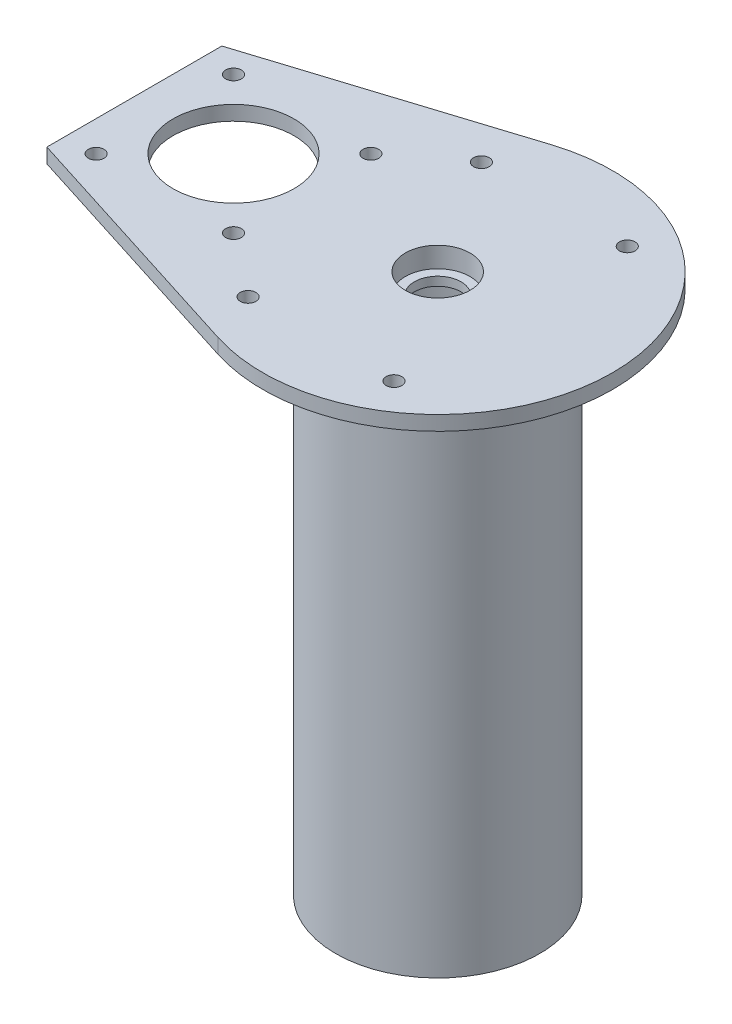
SolidWorks part; units mm, degrees
ref_plane "Front Plane" through (0, 0, 0) normal (0, 0, 1) x (1, 0, 0)
ref_plane "Top Plane" through (0, 0, 0) normal (0, 1, 0) x (1, 0, 0)
ref_plane "Right Plane" through (0, 0, 0) normal (1, 0, 0) x (0, 0, -1)
sketch "Sketch2" plane through (0, 0, 0) normal (0, 1, 0) x (1, 0, 0)
  line L0 (-104, -30) -> (-18.1154, -57.1999)
  line L2 (-104, -30) -> (-104, 30)
  line L5 (-93.55, 23.55) -> (-93.55, -23.55) construction
  line L6 (-93.55, -23.55) -> (-46.45, -23.55) construction
  line L7 (-104, 30) -> (-18.1154, 57.1999)
  line L8 (-46.45, -23.55) -> (-46.45, 23.55) construction
  line L9 (-46.45, 23.55) -> (-93.55, 23.55) construction
  arc A0 (-18.1154, -57.1999) -> (-18.1154, 57.1999) centre (0, 0) ccw
  circle A1 centre (-93.55, 23.55) radius 2.685
  circle A2 centre (-46.45, 23.55) radius 2.685
  circle A3 centre (-93.55, -23.55) radius 2.685
  circle A4 centre (-46.45, -23.55) radius 2.685
  circle A5 centre (0, 0) radius 11.1
  circle A6 centre (-70, 0) radius 20.75
  point P3 (-70, 0)
  dimension "D1" = 47.1
  dimension "D2" = 120
  dimension "D8" = 5.37
  dimension "D9" = 5.37
  dimension "D10" = 5.37
  dimension "D11" = 5.37
  dimension "D12" = 22.2
  dimension "D15" = 41.5
  dimension "D3" = 70
  dimension "D4" = 60
  dimension "D5" = 47.1
  dimension "D6" = 23.55
  dimension "D7" = 23.55
  dimension "D13" = 30
  dimension "D14" = 30
extrude "Boss-Extrude1" add sketch "Sketch2" along normal blind 5
sketch "Sketch3" plane through (0, 0, 0) normal (0, -1, 0) x (1, 0, 0)
  circle A0 centre (0, 0) radius 35
  circle A1 centre (0, 0) radius 30
  dimension "D1" = 60
  dimension "D2" = 70
extrude "Boss-Extrude2" add sketch "Sketch3" along normal blind 175
sketch "Sketch4" plane through (0, -175, 0) normal (0, -1, 0) x (1, 0, 0)
  circle A0 centre (0, 0) radius 35
  dimension "D1" = 70
extrude "Boss-Extrude3" add sketch "Sketch4" along normal blind 5
sketch "Sketch5" plane through (0, -180, 0) normal (0, -1, 0) x (1, 0, 0)
  circle A0 centre (0, 0) radius 11.1
  dimension "D1" = 22.2
sketch "Sketch6" plane through (0, -180, 0) normal (0, -1, 0) x (1, 0, 0)
  line L0 (15, 25.9808) -> (16.2754, 28.1899) construction
  line L1 (15, -25.9808) -> (16.3249, -28.2755) construction
  line L2 (20, 0) -> (32.3212, 0) construction
  arc A5 (10, -17.3205) -> (10, 17.3205) centre (0, 0) ccw
  arc A6 (15, -25.9808) -> (15, 25.9808) centre (0, 0) ccw
  arc A7 (15, 25.9808) -> (10, 17.3205) centre (12.5, 21.6506) ccw
  arc A8 (10, -17.3205) -> (15, -25.9808) centre (12.5, -21.6506) ccw
  dimension "D1" = 60
  dimension "D2" = 60
extrude "Cut-Extrude3" cut sketch "Sketch6" against normal blind 6
sketch "Sketch10" plane through (0, -175, 0) normal (0, 1, 0) x (1, 0, 0)
  circle A0 centre (0, 0) radius 16.1
extrude "Boss-Extrude5" add sketch "Sketch10" along normal blind 5
extrude "Cut-Extrude7" cut sketch "Sketch5" against normal blind 7
sketch "Sketch11" plane through (0, -173, 0) normal (0, -1, 0) x (1, 0, 0)
  circle A0 centre (0, 0) radius 8
extrude "Cut-Extrude8" cut sketch "Sketch11" against normal up to next
sketch "Sketch13" plane through (0, 0, 0) normal (0, -1, 0) x (1, 0, 0)
  circle A0 centre (0, 0) radius 11.1
  circle A1 centre (0, 0) radius 16.1
extrude "Boss-Extrude6" add sketch "Sketch13" along normal blind 2
sketch "Sketch14" plane through (0, -2, 0) normal (0, -1, 0) x (1, 0, 0)
  circle A0 centre (0, 0) radius 16.1
  circle A1 centre (0, 0) radius 8
extrude "Boss-Extrude7" add sketch "Sketch14" along normal blind 3
sketch "Sketch15" plane through (0, 5, 0) normal (0, 1, 0) x (1, 0, 0)
  line L0 (-55, 0) -> (55, 0) construction
  circle A0 centre (-25, 40) radius 2.685
  circle A1 centre (25, 40) radius 2.685
  circle A2 centre (25, -40) radius 2.685
  circle A3 centre (-25, -40) radius 2.685
  dimension "D5" = 5.37
  dimension "D6" = 5.37
  dimension "D1" = 40
  dimension "D2" = 40
  dimension "D3" = 25
  dimension "D4" = 25
extrude "Cut-Extrude9" cut sketch "Sketch15" against normal through all
